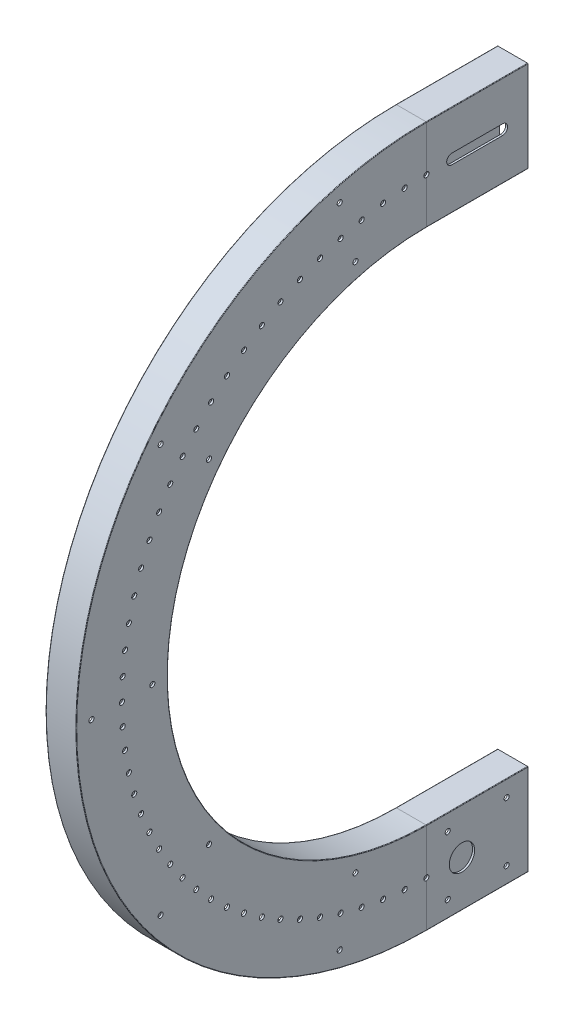
SolidWorks part; units mm, degrees
material "1060 Alloy"
ref_plane "Front Plane" through (0, 0, 0) normal (0, 0, 1) x (1, 0, 0)
ref_plane "Top Plane" through (0, 0, 0) normal (0, 1, 0) x (1, 0, 0)
ref_plane "Right Plane" through (0, 0, 0) normal (1, 0, 0) x (0, 0, -1)
sketch "Sketch2" plane through (0, 0, 0) normal (0, 0, 1) x (1, 0, 0)
  line L0 (0, -44.5) -> (0, 44.5)
  line L1 (-0.5, 45) -> (-29.5, 45)
  line L2 (-30, 44.5) -> (-30, 15)
  line L3 (-30, 15) -> (-28, 15)
  line L4 (-28, 15) -> (-28, 43)
  line L5 (-28, 43) -> (-2, 43)
  line L6 (-2, 43) -> (-2, -43)
  line L7 (-2, -43) -> (-28, -43)
  line L8 (-28, -43) -> (-28, -15)
  line L9 (-28, -15) -> (-30, -15)
  line L10 (-30, -15) -> (-30, -44.5)
  line L11 (-29.5, -45) -> (-0.5, -45)
  line L12 (0, -49.5) -> (0, 49.5) construction
  arc A0 (-30, -44.5) -> (-29.5, -45) centre (-29.5, -44.5) ccw
  arc A1 (0, -44.5) -> (-0.5, -45) centre (-0.5, -44.5) cw
  arc A2 (0, 44.5) -> (-0.5, 45) centre (-0.5, 44.5) ccw
  arc A3 (-29.5, 45) -> (-30, 44.5) centre (-29.5, 44.5) ccw
  point P4 (0, 0)
  point P16 (-30, -45)
  point P23 (-30, 45)
  dimension "D11" = 0.5
  dimension "D1" = 90
  dimension "D2" = 30
  dimension "D3" = 30
  dimension "D4" = 2
  dimension "D5" = 2
  dimension "D6" = 2
  dimension "D7" = 2
  dimension "D8" = 2
  dimension "D9" = 30
  dimension "D10" = 30
sketch "Sketch4" plane through (0, 0, 0) normal (1, 0, 0) x (0, 0, -1)
  line L0 (0, 0) -> (-100, 0)
  line L1 (-100, 0) -> (-100, 300) construction
  line L2 (-100, 600) -> (0, 600)
  arc A0 (-100, 0) -> (-100, 600) centre (-100, 300) cw
  dimension "D1" = 100
  dimension "D2" = 300
sweep "Sweep2" add profiles "Sketch2" path "Sketch4"
sketch "Sketch5" plane through (0, 0, 0) normal (1, 0, 0) x (0, 0, -1)
  line L0 (0, -44.5) -> (0, 44.5) construction
  line L1 (-50, 0) -> (-21.0086, -28.9914) construction
  line L2 (-50, 0) -> (-78.9914, -28.9914) construction
  line L3 (-50, 0) -> (-78.9914, 28.9914) construction
  line L4 (-50, 0) -> (-21.0086, 28.9914) construction
  line L5 (0, 44.5) -> (-100, 44.5) construction
  circle A0 centre (-50, 0) radius 41 construction
  circle A1 centre (-78.9914, 28.9914) radius 2.5
  circle A2 centre (-78.9914, -28.9914) radius 2.5
  circle A3 centre (-21.0086, 28.9914) radius 2.5
  circle A4 centre (-21.0086, -28.9914) radius 2.5
  circle A5 centre (-65, 0) radius 12.5
  point P8 (-50, 0)
  point P12 (-50, 0)
  dimension "D1" = 50
  dimension "D2" = 15
  dimension "D3" = 82
  dimension "D4" = 135
  dimension "D5" = 90
  dimension "D6" = 90
extrude "Cut-Extrude1" cut sketch "Sketch5" against normal blind 10
sketch "Sketch6" plane through (-30, 0, 0) normal (-1, 0, 0) x (0, 0, 1)
  line L0 (100, 300) -> (189.1632, -32.7614) construction
  line L1 (100, 300) -> (100, -44.5) construction
  arc A2 (100, -44.5) -> (100, 644.5) centre (100, 300) ccw construction
  circle A3 centre (169.8811, 39.2) radius 2.5
  circle A4 centre (185.4103, -18.7555) radius 2.5
  arc A5 (100, 45) -> (100, 555) centre (100, 300) ccw construction
  dimension "D2" = 5
  dimension "D3" = 5
  dimension "D1" = 15
  dimension "D4" = 270
  dimension "D5" = 60
extrude "Cut-Extrude2" cut sketch "Sketch6" against normal blind 30
pattern_circular "CirPattern1" count 5 every 37.5 about axis through (0, 300, 100) along (1, 0, 0) of "Cut-Extrude2"
sketch "Sketch7" plane through (-2, 0, 0) normal (-1, 0, 0) x (0, 0, 1)
  line L0 (75, 600.8859) -> (25, 600.8859) construction
  line L1 (75, 595.8859) -> (25, 595.8859)
  line L2 (75, 605.8859) -> (25, 605.8859)
  line L3 (0, 557) -> (0, 643) construction
  line L4 (100, 557) -> (100, 643) construction
  arc A0 (75, 595.8859) -> (75, 605.8859) centre (75, 600.8859) ccw
  arc A1 (25, 605.8859) -> (25, 595.8859) centre (25, 600.8859) ccw
  point P2 (50, 600.8859)
  dimension "D2" = 25
  dimension "D1" = 25
  dimension "D3" = 10
extrude "Cut-Extrude3" cut sketch "Sketch7" against normal blind 2
sketch "Sketch8" plane through (-2, 0, 0) normal (-1, 0, 0) x (0, 0, 1)
  line L0 (100, 300) -> (100, 0) construction
  circle A0 centre (100, 0) radius 2.5
  dimension "D1" = 5
  dimension "D2" = 300
extrude "Cut-Extrude4" cut sketch "Sketch8" against normal blind 10
pattern_circular "CirPattern2" count 45 over 180 about axis through (0, 300, 100) along (1, 0, 0) of "Cut-Extrude4"
